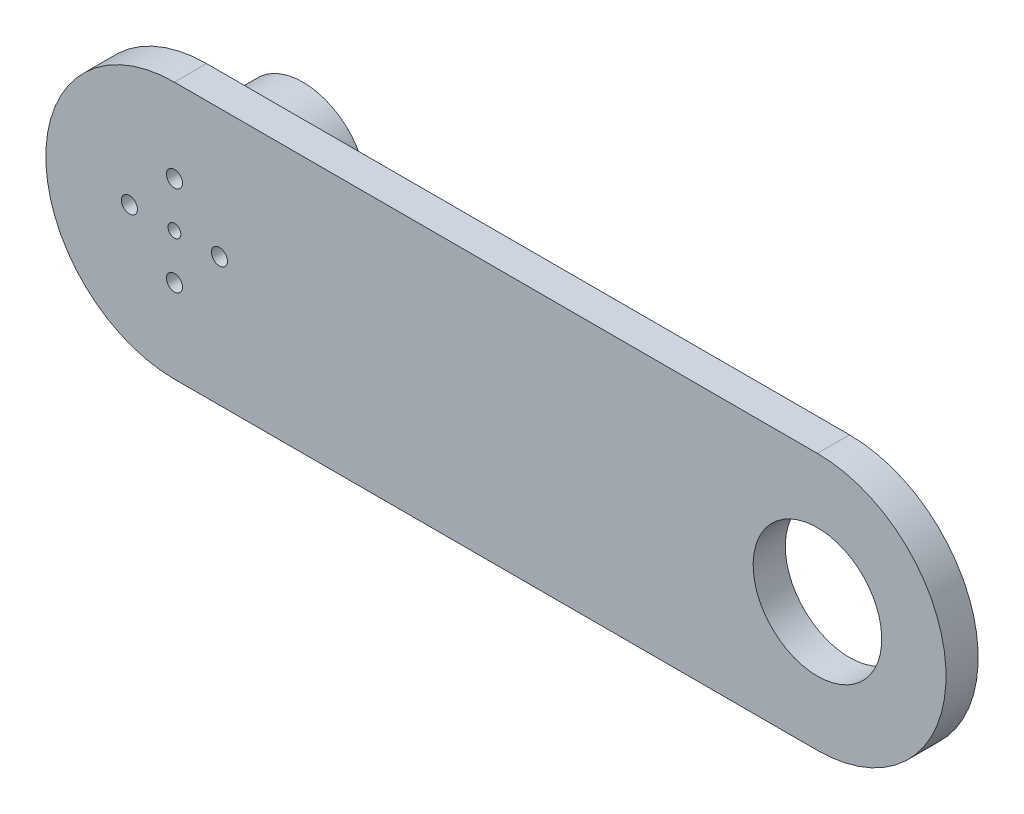
SolidWorks part; units mm, degrees
ref_plane "Front Plane" through (0, 0, 0) normal (0, 0, 1) x (1, 0, 0)
ref_plane "Top Plane" through (0, 0, 0) normal (0, 1, 0) x (1, 0, 0)
ref_plane "Right Plane" through (0, 0, 0) normal (1, 0, 0) x (0, 0, -1)
sketch "Sketch1" plane through (0, 0, 0) normal (0, 1, 0) x (1, 0, 0)
  line L0 (100, -20) -> (0, -20)
  line L2 (0, 20) -> (100, 20)
  arc A0 (0, 20) -> (0, -20) centre (0, 0) ccw
  arc A1 (100, -20) -> (100, 20) centre (100, 0) ccw
  dimension "D1" = 40
  dimension "D3" = 100
  dimension "D2" = 2
extrude "Boss-Extrude1" add sketch "Sketch1" along normal blind 5 contours L2 A1 L0 A0
sketch "Sketch2" plane through (0, 5, 0) normal (0, 1, 0) x (1, 0, 0)
  circle A0 centre (0, 0) radius 1
  circle A1 centre (0, 7) radius 1.25
  circle A2 centre (0.001, 0.001) radius 1
  circle A3 centre (7.001, 0.001) radius 1.25
  circle A4 centre (0.002, 0) radius 1
  circle A5 centre (0.002, -7) radius 1.25
  circle A6 centre (0.001, -0.001) radius 1
  circle A7 centre (-6.999, -0.001) radius 1.25
  point P20 (0.001, 0)
  dimension "D1" = 2
  dimension "D2" = 2.5
  dimension "D4" = 7
  dimension "D3" = 4
extrude "Cut-Extrude1" cut sketch "Sketch2" against normal up to next contours A1 | A0 | A3 | A5 | A7
sketch "Sketch3" plane through (0, 5, 0) normal (0, 1, 0) x (1, 0, 0)
  line L0 (100, 0) -> (120, 0) construction
  arc A0 (100, -20) -> (100, 20) centre (100, 0) ccw construction
  circle A5 centre (100, 0) radius 10
  dimension "D1" = 20
  dimension "D2" = 20
extrude "Cut-Extrude2" cut sketch "Sketch3" against normal up to next
sketch "Sketch4" plane through (0, 0, 0) normal (0, -1, 0) x (1, 0, 0)
  circle A0 centre (0, 0) radius 10
  dimension "D1" = 20
extrude "Boss-Extrude2" add sketch "Sketch4" along normal blind 15
move or copy body "Body-Move/Copy1" bodies to move or copy 110 copy no rotation origin (0, 0, 0) rotation axis (1, 0, 0) rotation angle 90
move or copy body "Body-Move/Copy2" bodies to move or copy 111 copy no translate (0, 0, -5)
